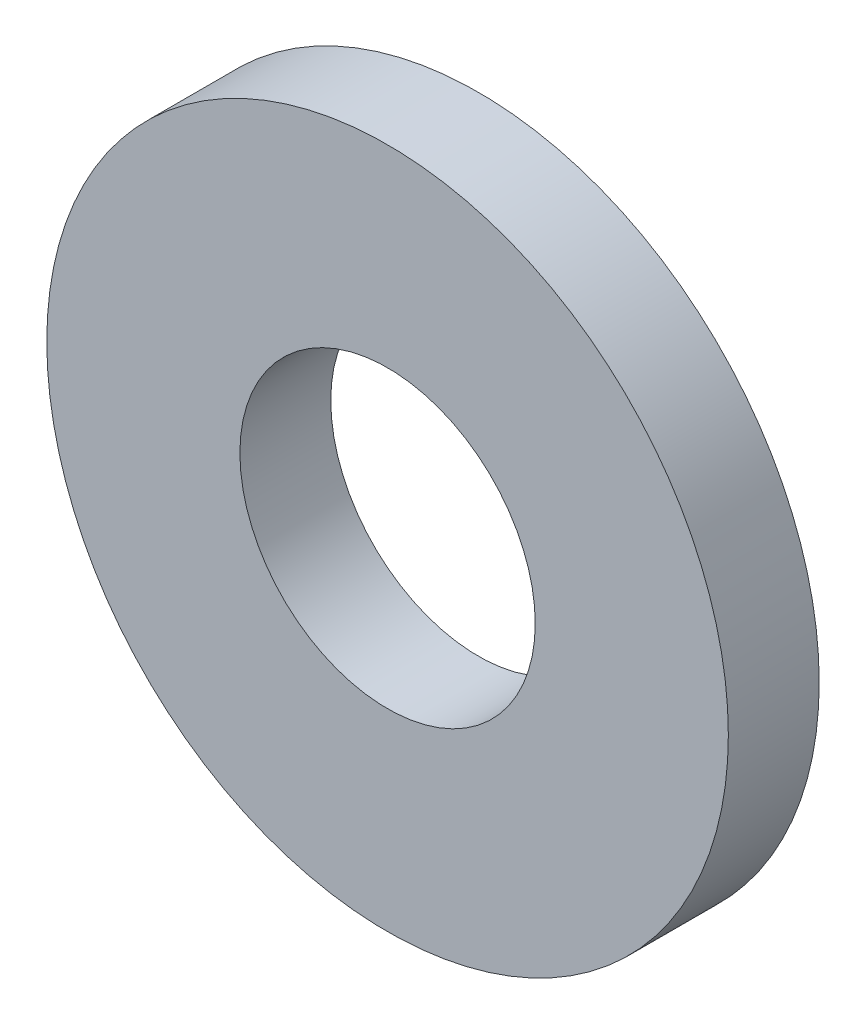
SolidWorks part; units mm, degrees
ref_plane "前视基准面" through (0, 0, 0) normal (0, 0, 1) x (1, 0, 0)
ref_plane "上视基准面" through (0, 0, 0) normal (0, 1, 0) x (1, 0, 0)
ref_plane "右视基准面" through (0, 0, 0) normal (1, 0, 0) x (0, 0, -1)
sketch "草图1" plane through (0, 0, 0) normal (0, 0, 1) x (1, 0, 0)
  circle A0 centre (0, 0) radius 7.5
  circle A1 centre (0, 0) radius 3.25
  dimension "D1" = 6.5
  dimension "D2" = 15
extrude "凸台-拉伸1" add sketch "草图1" along normal blind 2
